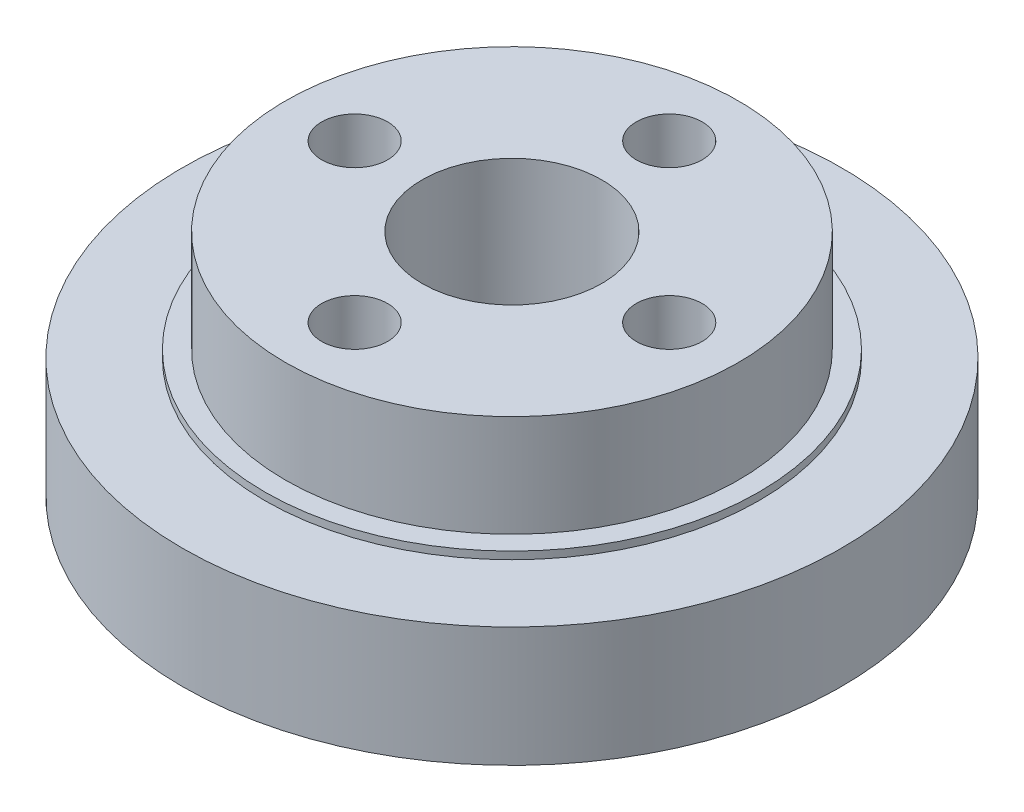
SolidWorks part; units mm, degrees
ref_plane "Front Plane" through (0, 0, 0) normal (0, 0, 1) x (1, 0, 0)
ref_plane "Top Plane" through (0, 0, 0) normal (0, 1, 0) x (1, 0, 0)
ref_plane "Right Plane" through (0, 0, 0) normal (1, 0, 0) x (0, 0, -1)
sketch "Sketch1" plane through (0, 0, 0) normal (0, 1, 0) x (1, 0, 0)
  circle A0 centre (0, 0) radius 22
  dimension "D1" = 44
extrude "Boss-Extrude1" add sketch "Sketch1" along normal blind 8
sketch "Sketch2" plane through (0, 8, 0) normal (0, 1, 0) x (1, 0, 0)
  circle A0 centre (0, 0) radius 16.5
  dimension "D1" = 33
extrude "Boss-Extrude2" add sketch "Sketch2" along normal blind 0.5
sketch "Sketch3" plane through (0, 8.5, 0) normal (0, 1, 0) x (1, 0, 0)
  circle A0 centre (0, 0) radius 15.125
  dimension "D1" = 30.25
extrude "Boss-Extrude3" add sketch "Sketch3" along normal blind 6.8
sketch "Sketch4" plane through (0, 15.3, 0) normal (0, 1, 0) x (1, 0, 0)
  circle A0 centre (0, 0) radius 6
  dimension "D1" = 12
extrude "Cut-Extrude1" cut sketch "Sketch4" against normal through all
sketch "Sketch5" plane through (0, 0, 0) normal (0, 1, 0) x (1, 0, 0)
  line L0 (0, 0) -> (26.2686, 0) construction
  line L1 (-8.415, 0) -> (8.415, 0) construction
  line L2 (0, 0) -> (26.9941, 4.2754) construction
  circle A0 centre (18.2722, 2.894) radius 1.6
  dimension "D2" = 3.2
  dimension "D1" = 9
  dimension "D3" = 18.5
extrude "Cut-Extrude2" cut sketch "Sketch5" along normal blind 7
pattern_circular "CirPattern1" count 6 over 360 about axis through (0, 0, 0) along (0, 1, 0) of "Cut-Extrude2"
sketch "Sketch6" plane through (0, 15.3, 0) normal (0, 1, 0) x (1, 0, 0)
  line L0 (-8.415, 0) -> (8.415, 0) construction
  circle A0 centre (10.5, 0) radius 2.2
  dimension "D1" = 4.4
  dimension "D2" = 10.5
extrude "Cut-Extrude3" cut sketch "Sketch6" against normal blind 5.5
pattern_circular "CirPattern2" count 4 over 360 about axis through (0, 0, 0) along (0, 1, 0) of "Cut-Extrude3"
equation "\"pin_circle_R\" = 27"
equation "\"ecc\" = 1.5"
equation "\"n_pins\" = 11"
equation "\"pin_d\" = 3"
equation "\"out_pin_R\" = 18.5"
equation "\"disc_clr\" = 0.1"
equation "\"seat_6803\" = 26.1"
equation "\"disc_t\" = 5"
equation "\"out_hole_clr\" = 0.5"
equation "\"boss_17\" = 17.15"
equation "\"rotor_bolt_R\" = 10"
equation "\"m25_clr\" = 2.8"
equation "\"m25_head\" = 5"
equation "\"insert_hole\" = 4.4"
equation "\"csk\" = 0.6"
equation "\"peg_d\" = 3.0"
equation "\"plug_d\" = 8.6"
equation "\"peg_clr\" = 0.3"
equation "\"m3_clr\" = 3.4"
equation "\"m3_head\" = 6.2"
equation "\"pin_press\" = 3.2"
equation "\"hub_30\" = 30.25"
equation "\"hub_short\" = 0.2"
equation "\"m3_tap\" = 2.8"
equation "\"D1@Sketch3\"=\"hub_30\""
equation "\"D1@Boss-Extrude3\"=7-\"hub_short\""
equation "\"D2@Sketch5\"=\"pin_press\""
equation "\"D3@Sketch5\"=\"out_pin_R\""
equation "\"D1@Sketch6\"=\"insert_hole\""
equation "\"seat_6806\" = 42.1"
equation "\"pin_slip\" = 3.3"
equation "\"rear_plate_t\" = 2"
